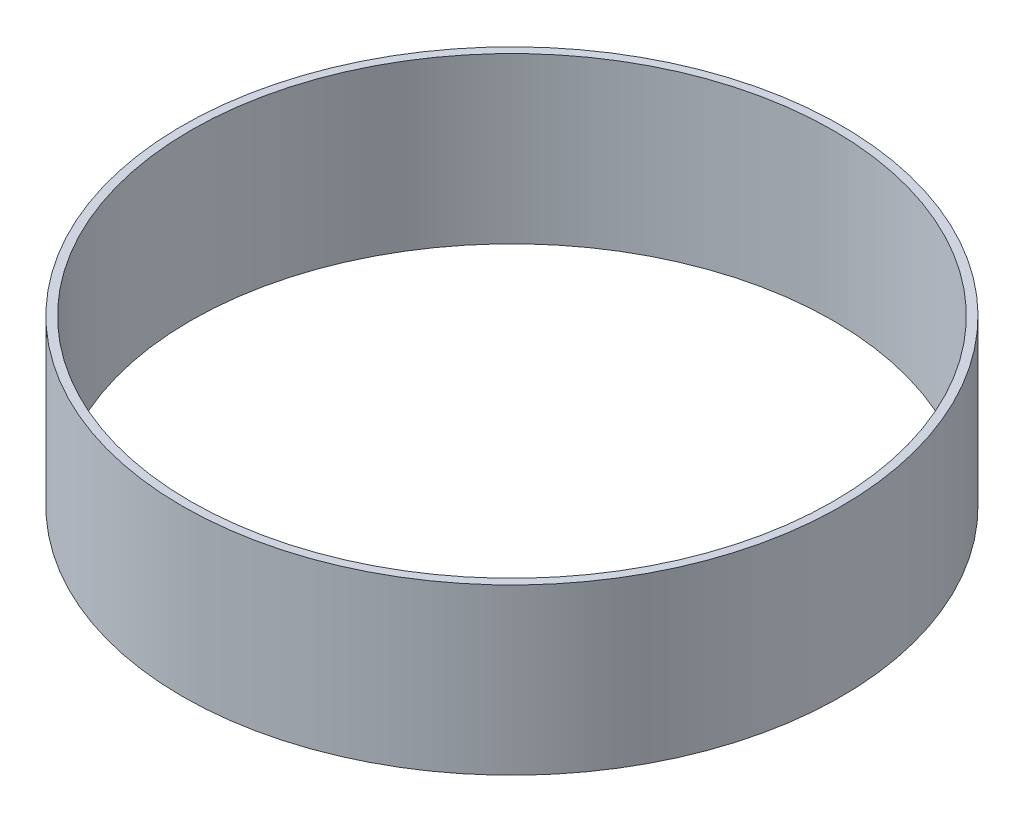
SolidWorks part; units mm, degrees
material "AISI 304"
ref_plane "Piano frontale" through (0, 0, 0) normal (0, 0, 1) x (1, 0, 0)
ref_plane "Piano superiore" through (0, 0, 0) normal (0, 1, 0) x (1, 0, 0)
ref_plane "Piano destro" through (0, 0, 0) normal (1, 0, 0) x (0, 0, -1)
sketch "Schizzo1" plane through (0, 0, 0) normal (0, 1, 0) x (1, 0, 0)
  circle A0 centre (0, 0) radius 60
extrude "Estrusione-Sottile1" add sketch "Schizzo1" along normal mid plane 30 thin thin type one direction reverse wall 1.5
